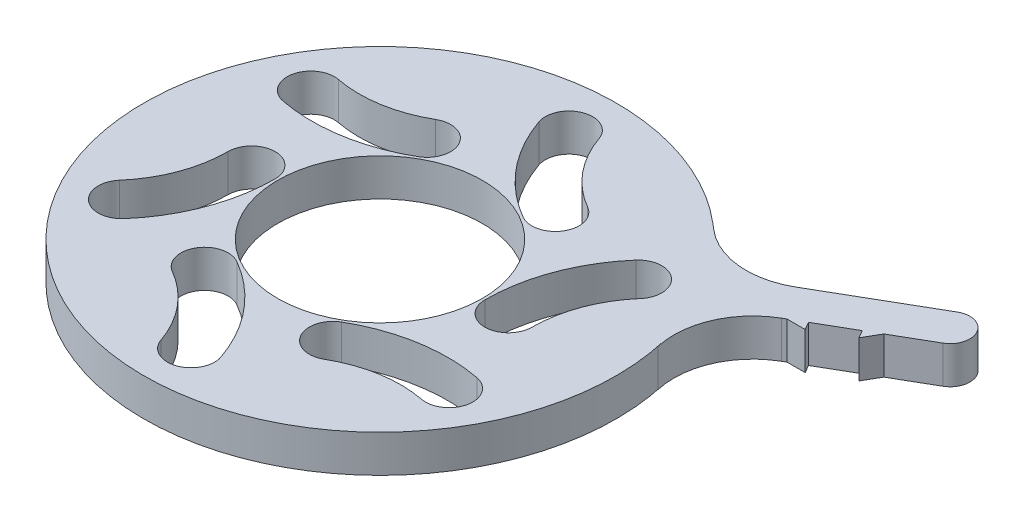
SolidWorks part; units mm, degrees
ref_plane "Plan de face" through (0, 0, 0) normal (0, 0, 1) x (1, 0, 0)
ref_plane "Plan de dessus" through (0, 0, 0) normal (0, 1, 0) x (1, 0, 0)
ref_plane "Plan de droite" through (0, 0, 0) normal (1, 0, 0) x (0, 0, -1)
sketch "Esquisse1" plane through (0, 0, 0) normal (0, 1, 0) x (1, 0, 0)
  line L0 (0, -55) -> (0, 55) construction
  line L1 (0, 0) -> (17.3205, 30) construction
  line L2 (0, 30) -> (17.3205, 30) construction
  circle A0 centre (0, 0) radius 30
  arc A1 (-2.8347, 23.018) -> (6.6554, 11.5274) centre (17.3205, 30) ccw
  arc A2 (2.8347, 24.982) -> (-2.8347, 23.018) centre (0, 24) ccw
  arc A3 (6.6554, 11.5274) -> (9.6554, 16.7236) centre (8.1554, 14.1255) ccw
  arc A4 (2.8347, 24.982) -> (9.6554, 16.7236) centre (17.3205, 30) ccw
  circle A5 centre (0, 0) radius 13
  arc A6 (23.0524, 10.036) -> (18.5168, 13.964) centre (20.7846, 12) ccw
  arc A7 (18.5168, 13.964) -> (13.3107, 0) centre (34.641, 0) ccw
  arc A8 (13.3107, 0) -> (19.3107, 0) centre (16.3107, 0) ccw
  arc A9 (23.0524, 10.036) -> (19.3107, 0) centre (34.641, 0) ccw
  arc A10 (20.2177, -14.9459) -> (21.3516, -9.0541) centre (20.7846, -12) ccw
  arc A11 (21.3516, -9.0541) -> (6.6554, -11.5274) centre (17.3205, -30) ccw
  arc A12 (6.6554, -11.5274) -> (9.6554, -16.7236) centre (8.1554, -14.1255) ccw
  arc A13 (20.2177, -14.9459) -> (9.6554, -16.7236) centre (17.3205, -30) ccw
  arc A14 (-2.8347, -24.982) -> (2.8347, -23.018) centre (0, -24) ccw
  arc A15 (2.8347, -23.018) -> (-6.6554, -11.5274) centre (-17.3205, -30) ccw
  arc A16 (-6.6554, -11.5274) -> (-9.6554, -16.7236) centre (-8.1554, -14.1255) ccw
  arc A17 (-2.8347, -24.982) -> (-9.6554, -16.7236) centre (-17.3205, -30) ccw
  arc A18 (-23.0524, -10.036) -> (-18.5168, -13.964) centre (-20.7846, -12) ccw
  arc A19 (-18.5168, -13.964) -> (-13.3107, 0) centre (-34.641, 0) ccw
  arc A20 (-13.3107, 0) -> (-19.3107, 0) centre (-16.3107, 0) ccw
  arc A21 (-23.0524, -10.036) -> (-19.3107, 0) centre (-34.641, 0) ccw
  arc A22 (-20.2177, 14.9459) -> (-21.3516, 9.0541) centre (-20.7846, 12) ccw
  arc A23 (-21.3516, 9.0541) -> (-6.6554, 11.5274) centre (-17.3205, 30) ccw
  arc A24 (-6.6554, 11.5274) -> (-9.6554, 16.7236) centre (-8.1554, 14.1255) ccw
  arc A25 (-20.2177, 14.9459) -> (-9.6554, 16.7236) centre (-17.3205, 30) ccw
  point P52 (0, 0)
  dimension "60" = 60
  dimension "D2" = 6
  dimension "D3" = 26
  dimension "D4" = 30
  dimension "D5" = 24
  dimension "D6" = 6
extrude "Boss.-Extru.1" add sketch "Esquisse1" along normal blind 4.75
sketch "Esquisse2" plane through (0, 4.75, 0) normal (0, 1, 0) x (1, 0, 0)
  line L0 (0, 0) -> (0, 67.265) construction
  line L1 (19.4487, 22.8418) -> (20.1838, 22.2159)
  line L2 (31.6667, 21.1696) -> (44.6571, 28.6696)
  line L3 (47.1571, 24.3394) -> (34.1667, 16.8394)
  line L4 (29.4301, 5.8994) -> (29.21, 6.8394)
  line L5 (1.1553, 0.667) -> (43.2148, 24.9501) construction
  arc A0 (31.6667, 21.1696) -> (20.1838, 22.2159) centre (26.6667, 29.8298) cw
  arc A1 (34.1667, 16.8394) -> (29.4301, 5.8994) centre (39.1667, 8.1792) ccw
  arc A2 (44.6571, 28.6696) -> (47.1571, 24.3394) centre (45.9071, 26.5045) cw
  circle A3 centre (0, 0) radius 30 construction
  arc A4 (19.4487, 22.8418) -> (29.21, 6.8394) centre (0, 0) cw
  dimension "D1" = 10
  dimension "D2" = 10
  dimension "D3" = 15
  dimension "D4" = 5
  dimension "D5" = 60
extrude "Boss.-Extru.2" add sketch "Esquisse2" against normal up to surface (4.75 mm away) up to face at (-18.4976, 0, 6.0187)
sketch "Esquisse3" plane through (0, 4.75, 0) normal (0, 1, 0) x (1, 0, 0)
  line L0 (34.5998, 17.0894) -> (36.9092, 17.0894)
  line L2 (36.9092, 17.0894) -> (36.3318, 18.0894)
  line L3 (36.3318, 18.0894) -> (34.5998, 17.0894)
  line L4 (32.7802, 29.241) -> (41.3, 14.4842) construction
  line L5 (40.6619, 20.5894) -> (42.394, 21.5894)
  line L6 (41.2393, 19.5894) -> (40.6619, 20.5894)
  line L7 (42.394, 21.5894) -> (41.2393, 19.5894)
  line L8 (34.1667, 16.8394) -> (47.1571, 24.3394) construction
  arc A1 (47.1571, 24.3394) -> (44.6571, 28.6696) centre (45.9071, 26.5045) ccw construction
  point P2 (51.8397, 23.7378)
  point P10 (41.1901, 28.0012)
  point P14 (0, 0)
  point P15 (43.3581, 27.9196)
  point P17 (44.7034, 16.4842)
  dimension "D1" = 5
  dimension "D2" = 30
  dimension "D3" = 2
  dimension "D4" = 10
extrude "Boss.-Extru.3" add sketch "Esquisse3" against normal up to surface (4.75 mm away) up to face at (-18.4976, 0, 6.0187)
